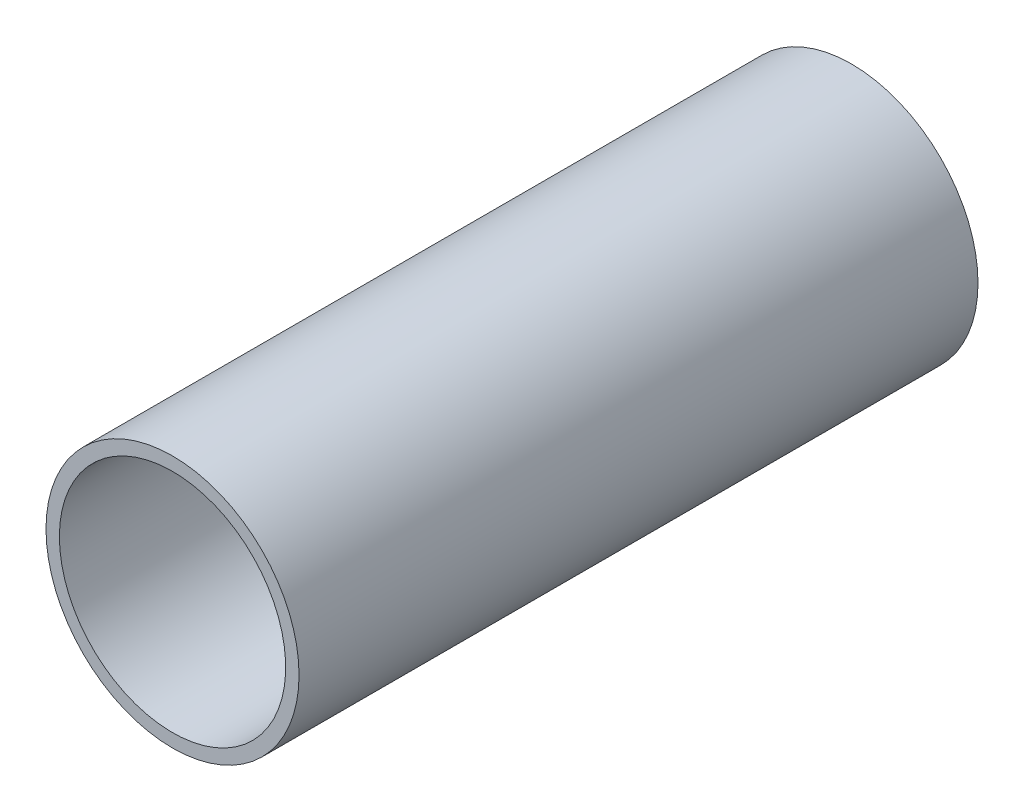
SolidWorks part; units mm, degrees
ref_plane "Front Plane" through (0, 0, 0) normal (0, 0, 1) x (1, 0, 0)
ref_plane "Top Plane" through (0, 0, 0) normal (0, 1, 0) x (1, 0, 0)
ref_plane "Right Plane" through (0, 0, 0) normal (1, 0, 0) x (0, 0, -1)
sketch "Sketch1" plane through (0, 0, 0) normal (0, 0, 1) x (1, 0, 0)
  circle A0 centre (0, 0) radius 25.4
  circle A1 centre (0, 0) radius 28.4
  dimension "D1" = 3
extrude "Boss-Extrude1" add sketch "Sketch1" along normal blind 152.4
